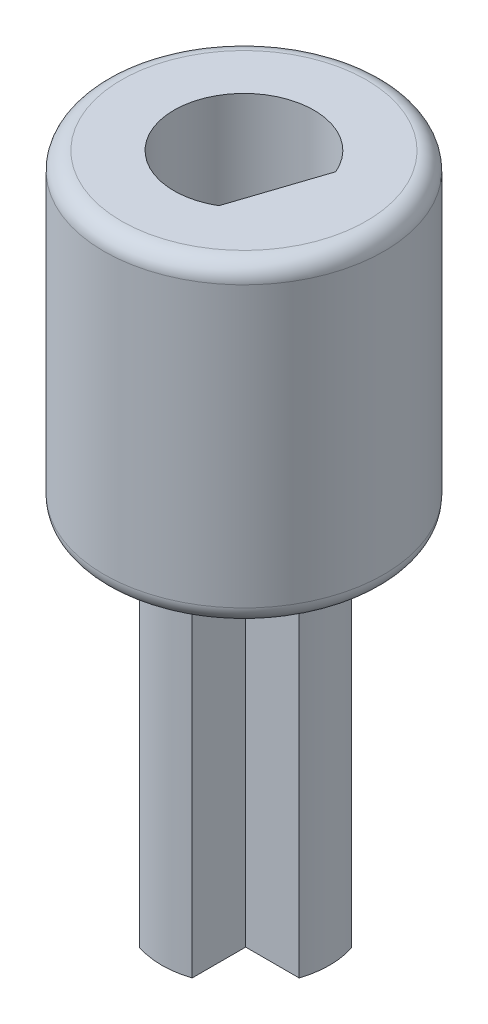
SolidWorks part; units mm, degrees
ref_plane "Plano frontal" through (0, 0, 0) normal (0, 0, 1) x (1, 0, 0)
ref_plane "Plano superior" through (0, 0, 0) normal (0, 1, 0) x (1, 0, 0)
ref_plane "Plano direito" through (0, 0, 0) normal (1, 0, 0) x (0, 0, -1)
sketch "Esboço1" plane through (0, 0, 0) normal (0, 1, 0) x (1, 0, 0)
  line L0 (-17.6155, 12.2276) -> (-17.6155, 13.7574)
  line L2 (-19.1155, 13.7276) -> (-19.1155, 12.2276)
  line L3 (-17.6155, 13.7574) -> (-17.6155, 12.2276)
  line L4 (-17.6155, 13.7276) -> (-17.6155, 12.2276)
  line L5 (-19.1155, 10.7276) -> (-20.6453, 10.7276)
  line L7 (-19.1155, 12.2276) -> (-20.6453, 12.2276)
  line L8 (-19.1155, 13.7276) -> (-19.1155, 12.2276)
  line L9 (-19.1155, 9.1978) -> (-19.1155, 10.7276)
  line L10 (-19.1155, 10.7276) -> (-19.1155, 9.2276)
  line L12 (-17.6155, 10.7276) -> (-17.6155, 9.2276)
  line L13 (-19.1155, 12.2276) -> (-20.6155, 12.2276)
  line L14 (-17.6155, 10.7276) -> (-17.6155, 9.1978)
  line L15 (-19.1155, 10.7276) -> (-20.6155, 10.7276)
  line L17 (-17.6155, 12.2276) -> (-16.0857, 12.2276)
  line L18 (-19.1155, 10.7276) -> (-19.1155, 9.1978)
  line L19 (-17.6155, 10.7276) -> (-16.0857, 10.7276)
  line L20 (-19.1155, 12.2276) -> (-19.1155, 13.7574)
  arc A0 (-16.0857, 10.7276) -> (-16.0857, 12.2276) centre (-18.3655, 11.4776) ccw
  arc A1 (-17.6155, 13.7574) -> (-19.1155, 13.7574) centre (-18.3655, 11.4776) ccw
  arc A2 (-19.1155, 9.1978) -> (-17.6155, 9.1978) centre (-18.3655, 11.4776) ccw
  arc A3 (-20.6453, 12.2276) -> (-20.6453, 10.7276) centre (-18.3655, 11.4776) ccw
extrude "Ressalto-extrusão1" add sketch "Esboço1" along normal blind 10 contours L7 A3 L5 L9 A2 L14 L12 L19 A0 L17 L0 L3 A1 L20 L2
sketch "Esboço7" plane through (0, 10, 0) normal (0, 1, 0) x (1, 0, 0)
  line L0 (-17.6155, 12.2276) -> (-17.6155, 13.7574) construction
  circle A0 centre (-18.3655, 11.4284) radius 4
  dimension "D1" = 0.75
extrude "Ressalto-extrusão3" add sketch "Esboço7" along normal blind 9
sketch "Esboço9" plane through (0, 19, 0) normal (0, 1, 0) x (1, 0, 0)
  line L0 (-17.3558, 9.702) -> (-16.5264, 12.2144)
  arc A2 (-16.5264, 12.2144) -> (-17.3558, 9.702) centre (-18.3655, 11.4284) ccw
  dimension "D1" = 1.5
extrude "Corte-extrusão2" cut sketch "Esboço9" against normal blind 7.5
fillet "Filete9" radius 0.5 14 edges at (-19.8804, 10, -10.7276) (-19.1155, 10, -9.9627) (-18.3655, 10, -9.0776) (-17.6155, 10, -9.9627) (-16.8506, 10, -10.7276) (-15.9655, 10, -11.4776) (-16.8506, 10, -12.2276) (-17.6155, 10, -12.9925) (-19.1155, 10, -12.9925) (-18.3655, 10, -13.8776) (-20.7655, 10, -11.4776) (-19.8804, 10, -12.2276) (-18.3655, 19, -7.4284) (-18.3655, 10, -7.4284)
